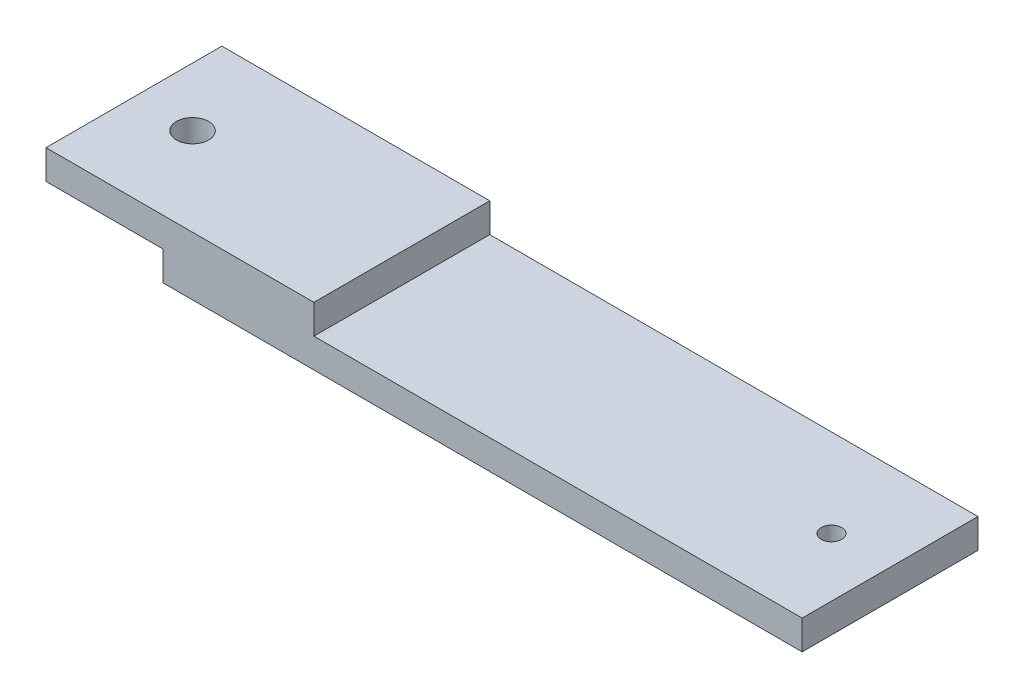
SolidWorks part; units mm, degrees
ref_plane "前视基准面" through (0, 0, 0) normal (0, 0, 1) x (1, 0, 0)
ref_plane "上视基准面" through (0, 0, 0) normal (0, 1, 0) x (1, 0, 0)
ref_plane "右视基准面" through (0, 0, 0) normal (1, 0, 0) x (0, 0, -1)
sketch "草图1" plane through (0, 0, 0) normal (0, 1, 0) x (1, 0, 0)
  line L0 (-24.1313, -2.1139) -> (104.8687, -2.1139) construction
  line L1 (-24.1313, 12.8861) -> (104.8687, 12.8861)
  line L2 (-24.1313, 12.8861) -> (-24.1313, -17.1139)
  line L3 (-24.1313, -17.1139) -> (104.8687, -17.1139)
  line L4 (104.8687, 12.8861) -> (104.8687, -17.1139)
  line L5 (-24.1313, 12.8861) -> (104.8687, -17.1139) construction
  line L6 (-24.1313, -17.1139) -> (104.8687, 12.8861) construction
  circle A0 centre (-14.1313, -2.1139) radius 2.75
  circle A1 centre (94.8687, -2.1139) radius 1.75
  point P4 (40.3687, -2.1139)
  dimension "D3" = 5.5
  dimension "D4" = 3.5
  dimension "D1" = 129
  dimension "D2" = 30
  dimension "D5" = 10
  dimension "D6" = 10
extrude "凸台-拉伸1" add sketch "草图1" along normal blind 10
sketch "草图2" plane through (0, 0, 17.1139) normal (0, 0, 1) x (1, 0, 0)
  line L1 (-24.1313, 5) -> (-4.1313, 5)
  line L2 (-24.1313, 5) -> (-24.1313, 0)
  line L3 (-24.1313, 0) -> (-4.1313, 0)
  line L4 (-4.1313, 5) -> (-4.1313, 0)
  line L5 (-24.1313, 5) -> (-4.1313, 0) construction
  line L6 (-24.1313, 0) -> (-4.1313, 5) construction
  line L7 (21.5731, 10) -> (104.8687, 10)
  line L8 (21.5731, 10) -> (21.5731, 5)
  line L9 (21.5731, 5) -> (104.8687, 5)
  line L10 (104.8687, 10) -> (104.8687, 5)
  line L11 (21.5731, 10) -> (104.8687, 5) construction
  line L12 (21.5731, 5) -> (104.8687, 10) construction
  point P4 (-14.1313, 2.5)
  point P9 (63.2209, 7.5)
  point P10 (-24.1313, 0)
  point P11 (104.8687, 10)
  dimension "D1" = 20
  dimension "D2" = 5
  dimension "D3" = 5
extrude "切除-拉伸1" cut sketch "草图2" against normal through all
